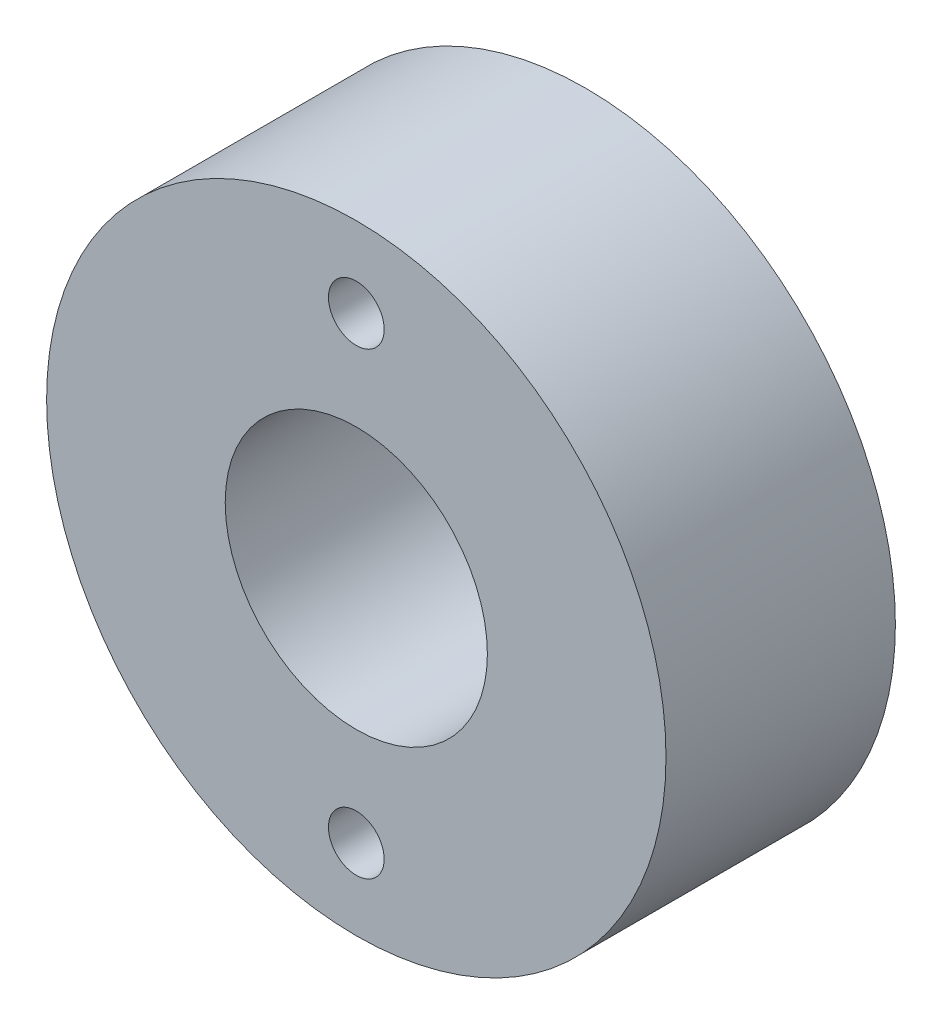
SolidWorks part; units mm, degrees
ref_plane "Front Plane" through (0, 0, 0) normal (0, 0, 1) x (1, 0, 0)
ref_plane "Top Plane" through (0, 0, 0) normal (0, 1, 0) x (1, 0, 0)
ref_plane "Right Plane" through (0, 0, 0) normal (1, 0, 0) x (0, 0, -1)
sketch "Sketch1" plane through (0, 0, 0) normal (0, 0, 1) x (1, 0, 0)
  circle A0 centre (0, 0) radius 9.45
extrude "Boss-Extrude1" add sketch "Sketch1" along normal blind 7
sketch "Sketch2" plane through (0, 0, 7) normal (0, 0, 1) x (1, 0, 0)
  circle A0 centre (0, 0) radius 4
extrude "Cut-Extrude1" cut sketch "Sketch2" against normal up to next
sketch "Sketch3" plane through (0, 0, 7) normal (0, 0, 1) x (1, 0, 0)
  point P0 (0, 7)
  point P2 (0, -7)
  point P5 (0, 0)
  point P6 (0, 0)
hole_wizard "Tap Drill for M2.5x0.45 Tap1" positions "Sketch3" profile "Sketch4" hole size "M2.5x0.45" standard "JIS" end condition up to next
sketch "Sketch4" plane through (0, 7, 7) normal (1, 0, 0) x (0, -1, 0)
  line L0 (0, 0) -> (0, 7)
  line L1 (0, 7) -> (0.85, 7)
  line L2 (0.85, 7) -> (0.85, 0)
  line L5 (0.85, 0) -> (0, 0)
  line L11 (0, -6.35) -> (0, 107.95) construction
  dimension "Thru Hole Dia." = 1.7
  dimension "Thru Hole Depth" = 7
